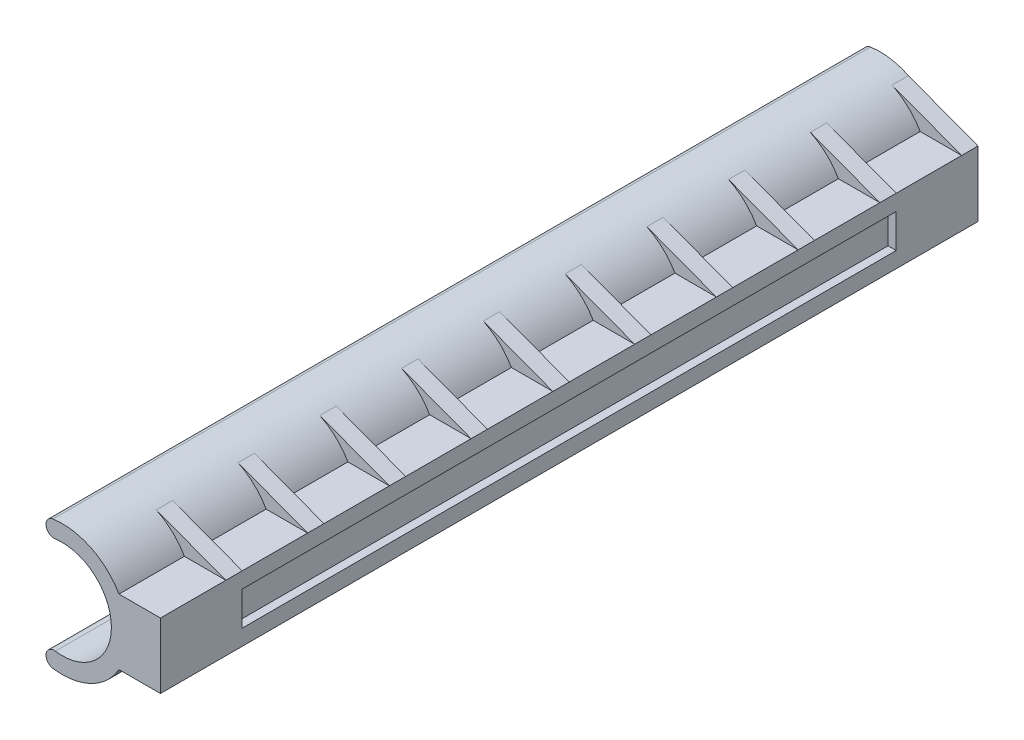
SolidWorks part; units mm, degrees
ref_plane "Front Plane" through (0, 0, 0) normal (0, 0, 1) x (1, 0, 0)
ref_plane "Top Plane" through (0, 0, 0) normal (0, 1, 0) x (1, 0, 0)
ref_plane "Right Plane" through (0, 0, 0) normal (1, 0, 0) x (0, 0, -1)
sketch "Sketch1" plane through (0, 0, 0) normal (0, 0, 1) x (1, 0, 0)
  line L2 (0, 0) -> (-5, 0) construction
  line L3 (-5, -34.641) -> (-5, 34.641) construction
  circle A4 centre (0, 0) radius 35 construction
  arc A8 (-5.7143, 39.5897) -> (-4.2857, 29.6923) centre (-5, 34.641) ccw
  arc A9 (-4.2857, -29.6923) -> (-5.7143, -39.5897) centre (-5, -34.641) ccw
  arc A10 (-5.7143, -39.5897) -> (-5.7143, 39.5897) centre (0, 0) ccw
  arc A11 (-4.2857, -29.6923) -> (-4.2857, 29.6923) centre (0, 0) ccw
  point P7 (0, 0)
  point P16 (-5, 0)
  dimension "D4" = 5
extrude "Boss-Extrude1" add sketch "Sketch1" along normal blind 500 contours A10 A8 A11 A9
sketch "Sketch2" plane through (0, 0, 0) normal (1, 0, 0) x (0, 0, -1)
  line L0 (0, 0) -> (-500, 0)
  line L1 (-500, 40) -> (-500, -40) construction
  line L2 (0, -40) -> (0, 40) construction
  line L3 (-500, -20) -> (0, -20)
  line L4 (-500, -20) -> (-500, 20)
  line L5 (-500, 20) -> (0, 20)
  line L6 (0, -20) -> (0, 20)
  line L7 (-500, -20) -> (0, 20) construction
  line L8 (-500, 20) -> (0, -20) construction
  point P6 (-250, 0)
  dimension "D1" = 40
extrude "Boss-Extrude2" add sketch "Sketch2" along normal blind 30 from offset 30 contours L4 L3 L6 L5
sketch "Sketch4" plane through (0, 0, 0) normal (0, 0, -1) x (-1, 0, 0)
  line L0 (-60, 20) -> (-17.4679, 35.9843)
  arc A0 (5.7143, 39.5897) -> (-34.641, 20) centre (0, 0) ccw construction
rib "Rib1" sketch "Sketch4" sketch "Sketch4" thickness 10 extrusion direction parallel to sketch draft on no parameters "D1"=10
pattern_linear "LPattern1" count 10 spacing 50 along (0, 0, 1) of "Rib1"
mirror "Mirror1" about plane through (0, 0, 0) normal (0, 1, 0) of "LPattern1", "Rib1"
sketch "Sketch5" plane through (60, 0, 0) normal (1, 0, 0) x (0, 0, -1)
  line L0 (0, 0) -> (-500, 0) construction
  line L1 (0, -20) -> (0, 20) construction
  line L2 (-500, -20) -> (-500, 20) construction
  line L4 (-450, -10.3502) -> (-50, -10.3502)
  line L5 (-450, -10.3502) -> (-450, 10.3502)
  line L6 (-450, 10.3502) -> (-50, 10.3502)
  line L7 (-50, -10.3502) -> (-50, 10.3502)
  line L8 (-450, -10.3502) -> (-50, 10.3502) construction
  line L9 (-450, 10.3502) -> (-50, -10.3502) construction
  point P6 (-250, 0)
  dimension "D1" = 400
extrude "Cut-Extrude1" cut sketch "Sketch5" against normal blind 5
